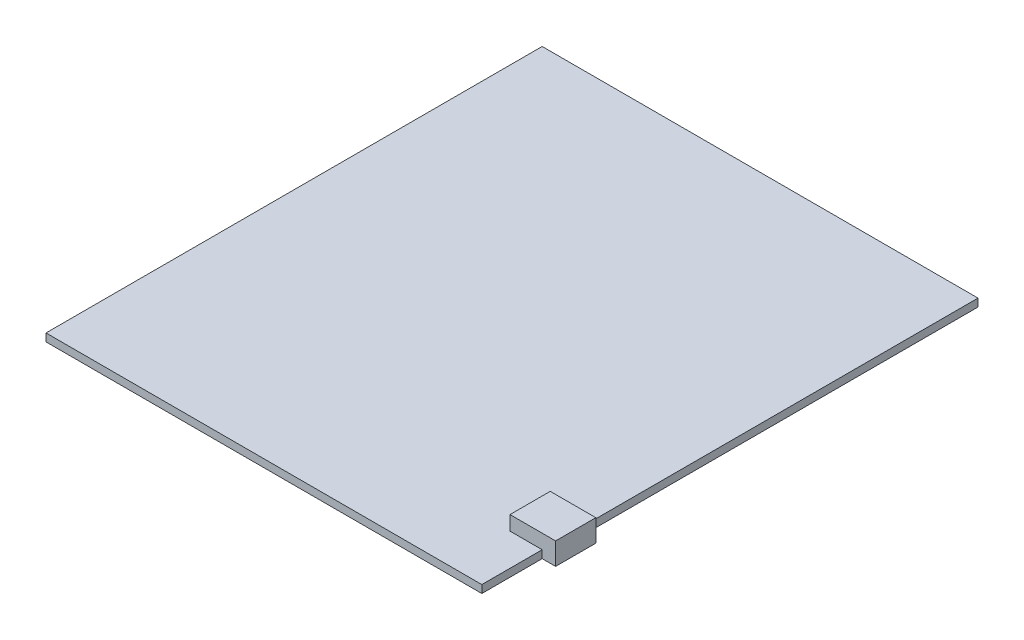
SolidWorks part; units mm, degrees
ref_plane "Front Plane" through (0, 0, 0) normal (0, 0, 1) x (1, 0, 0)
ref_plane "Top Plane" through (0, 0, 0) normal (0, 1, 0) x (1, 0, 0)
ref_plane "Right Plane" through (0, 0, 0) normal (1, 0, 0) x (0, 0, -1)
sketch "Sketch1" plane through (0, 0, 0) normal (0, 1, 0) x (1, 0, 0)
  line L1 (-41.275, -46.99) -> (41.275, -46.99)
  line L2 (-41.275, -46.99) -> (-41.275, 46.99)
  line L3 (-41.275, 46.99) -> (41.275, 46.99)
  line L4 (41.275, -46.99) -> (41.275, 46.99)
  line L5 (-41.275, -46.99) -> (41.275, 46.99) construction
  line L6 (-41.275, 46.99) -> (41.275, -46.99) construction
  point P0 (0, 0)
  dimension "D1" = 82.55
  dimension "D2" = 93.98
extrude "Boss-Extrude1" add sketch "Sketch1" along normal blind 1.4732
sketch "Sketch2" plane through (0, 0, 0) normal (0, 1, 0) x (1, 0, 0)
  line L1 (35.179, -35.56) -> (43.815, -35.56)
  line L2 (35.179, -35.56) -> (35.179, -27.94)
  line L3 (35.179, -27.94) -> (43.815, -27.94)
  line L4 (43.815, -35.56) -> (43.815, -27.94)
  line L5 (35.179, -35.56) -> (43.815, -27.94) construction
  line L6 (35.179, -27.94) -> (43.815, -35.56) construction
  line L7 (-41.275, -46.99) -> (41.275, -46.99) construction
  line L8 (41.275, -46.99) -> (41.275, 46.99) construction
  point P0 (39.497, -31.75)
  dimension "D1" = 8.636
  dimension "D2" = 7.62
  dimension "D3" = 19.05
  dimension "D4" = 6.096
extrude "Boss-Extrude2" add sketch "Sketch2" along normal blind 4.191
sketch "Sketch3" plane through (0, 0, 0) normal (0, -1, 0) x (1, 0, 0)
  line L1 (-31.75, -38.1) -> (31.75, -38.1) construction
  line L2 (-31.75, -38.1) -> (-31.75, 38.1) construction
  line L3 (-31.75, 38.1) -> (31.75, 38.1) construction
  line L4 (31.75, -38.1) -> (31.75, 38.1) construction
  line L5 (-31.75, -38.1) -> (31.75, 38.1) construction
  line L6 (-31.75, 38.1) -> (31.75, -38.1) construction
  circle A0 centre (-31.75, 38.1) radius 4.7625
  circle A1 centre (31.75, 38.1) radius 4.7625
  circle A2 centre (-31.75, -38.1) radius 4.7625
  circle A3 centre (31.75, -38.1) radius 4.7625
  point P0 (0, 0)
  dimension "D1" = 9.525
  dimension "D2" = 63.5
  dimension "D3" = 76.2
extrude "Boss-Extrude3" add sketch "Sketch3" along normal blind 3.6068
